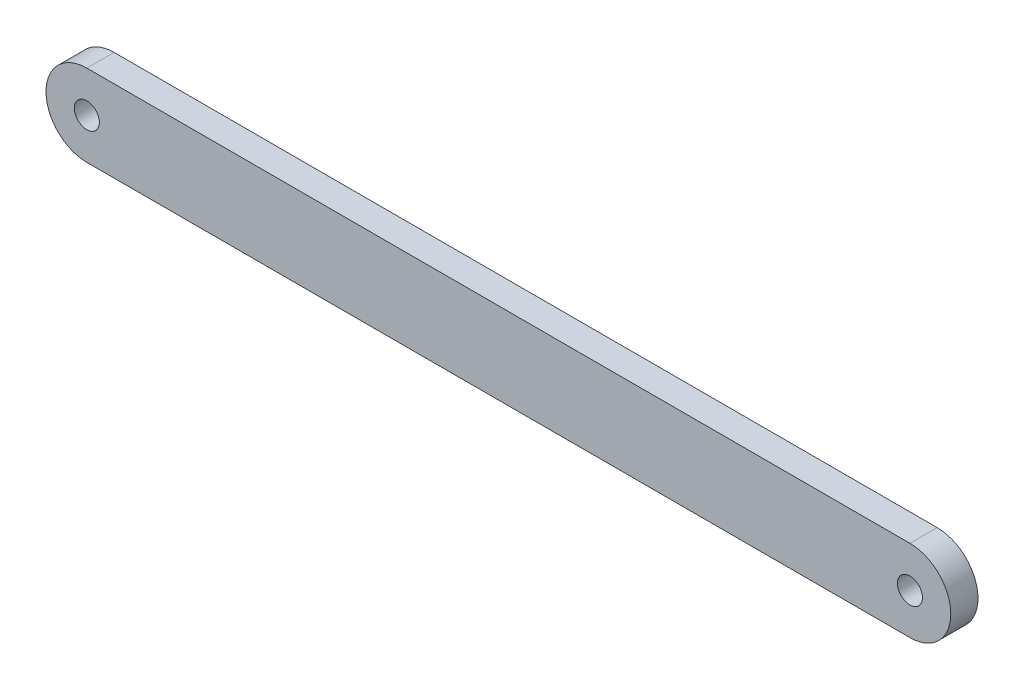
SolidWorks part; units mm, degrees
ref_plane "前视基准面" through (0, 0, 0) normal (0, 0, 1) x (1, 0, 0)
ref_plane "上视基准面" through (0, 0, 0) normal (0, 1, 0) x (1, 0, 0)
ref_plane "右视基准面" through (0, 0, 0) normal (1, 0, 0) x (0, 0, -1)
other "Configuration Table"
sketch "草图1" plane through (0, 0, 0) normal (0, 0, 1) x (1, 0, 0)
  line L1 (-75.6, 7.5) -> (75.6, 7.5)
  line L3 (-75.6, -7.5) -> (75.6, -7.5)
  line L5 (-75.6, 7.5) -> (75.6, -7.5) construction
  line L6 (-75.6, -7.5) -> (75.6, 7.5) construction
  arc A0 (-75.6, 7.5) -> (-75.6, -7.5) centre (-75.6, 0) ccw
  arc A1 (75.6, 7.5) -> (75.6, -7.5) centre (75.6, 0) cw
  circle A2 centre (-75.6, 0) radius 2.3
  circle A3 centre (75.6, 0) radius 2.3
  point P0 (0, 0)
  dimension "D1" = 4.6
  dimension "D2" = 4.6
  dimension "D3" = 151.2
  dimension "D4" = 15
extrude "凸台-拉伸1" add sketch "草图1" along normal blind 5
equation "\"fi\"=4.6"
equation "\"D1@草图1\"=\"fi\""
equation "\"D2@草图1\"=\"fi\""
equation "\"b0\"= 75.6'ground"
equation "\"D3@草图1\"=\"b4\""
equation "\"width\"=15"
equation "\"D4@草图1\"=\"width\""
equation "\"depth\"=5"
equation "\"D1@凸台-拉伸1\"=\"depth\""
equation "\"b1\"= \"b0\" *1.4/ 2'rocker"
equation "\"b2\"= \"b0\"'coupler"
equation "\"b3\"= \"b0\" / 2'coupler"
equation "\"b4\"= \"b0\" *2'leg"
equation "\"angle\"= 90度'左右cranker夹角"
equation "\"b5\"=(\"b2\"^2+\"b4\"^2)^0.5'斜边"
